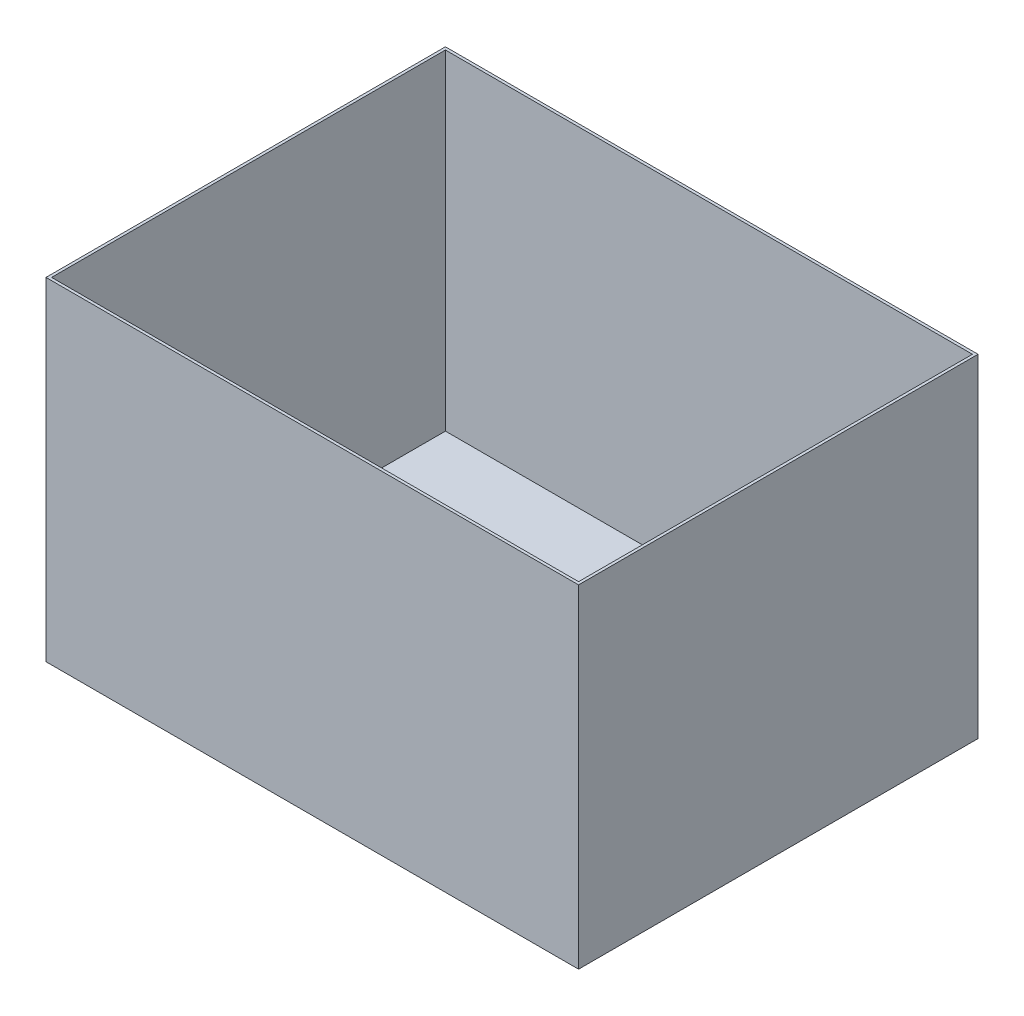
SolidWorks part; units mm, degrees
material "PPE"
ref_plane "Front Plane" through (0, 0, 0) normal (0, 0, 1) x (1, 0, 0)
ref_plane "Top Plane" through (0, 0, 0) normal (0, 1, 0) x (1, 0, 0)
ref_plane "Right Plane" through (0, 0, 0) normal (1, 0, 0) x (0, 0, -1)
sketch "Sketch1" plane through (0, 0, 0) normal (0, 1, 0) x (1, 0, 0)
  line L1 (-609.6, 457.2) -> (609.6, 457.2)
  line L2 (-609.6, 457.2) -> (-609.6, -457.2)
  line L3 (-609.6, -457.2) -> (609.6, -457.2)
  line L4 (609.6, 457.2) -> (609.6, -457.2)
  line L5 (-609.6, 457.2) -> (609.6, -457.2) construction
  line L6 (-609.6, -457.2) -> (609.6, 457.2) construction
  point P0 (0, 0)
  dimension "D1" = 1219.2
  dimension "D2" = 914.4
extrude "Boss-Extrude1" add sketch "Sketch1" along normal blind 762
shell "Shell1" thickness 6.35
